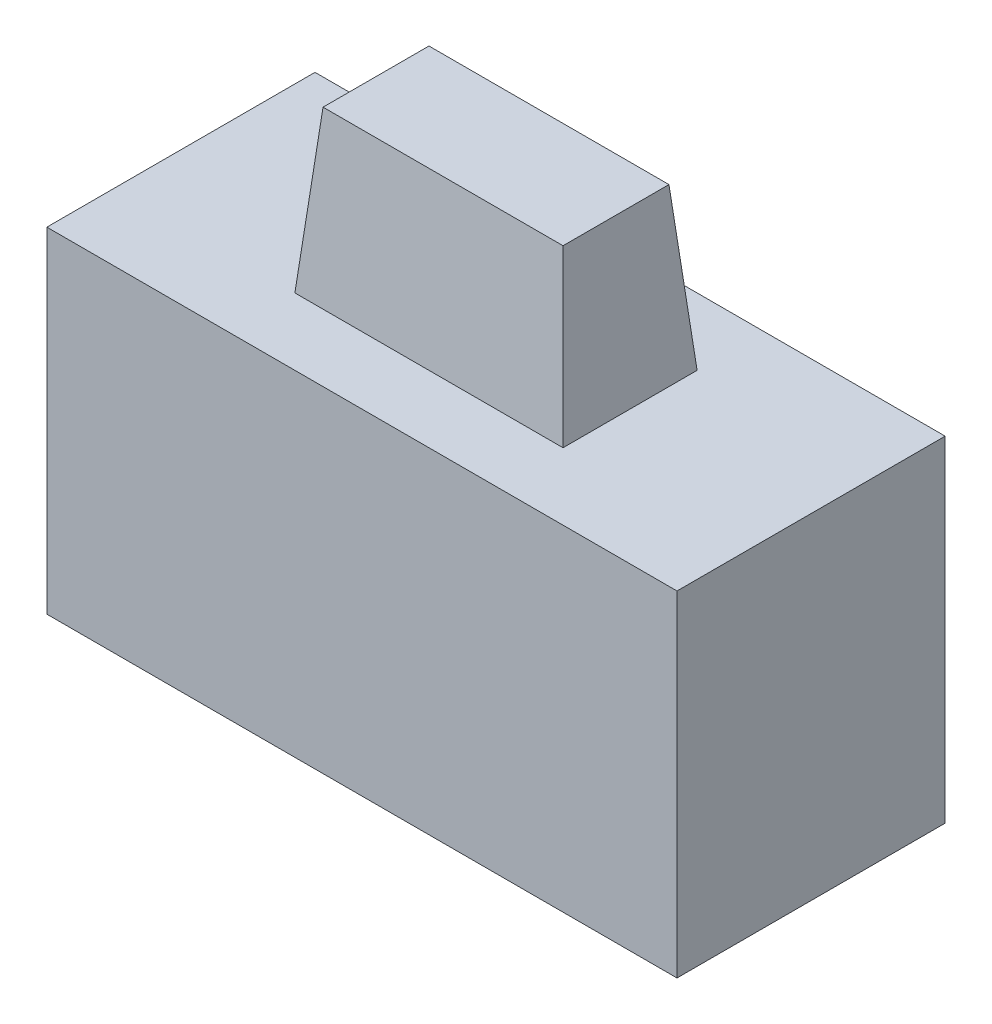
SolidWorks part; units mm, degrees
ref_plane "Front Plane" through (0, 0, 0) normal (0, 0, 1) x (1, 0, 0)
ref_plane "Top Plane" through (0, 0, 0) normal (0, 1, 0) x (1, 0, 0)
ref_plane "Right Plane" through (0, 0, 0) normal (1, 0, 0) x (0, 0, -1)
sketch "Sketch1" plane through (0, 0, 0) normal (0, 0, 1) x (1, 0, 0)
  line L1 (-2.35, 0) -> (2.35, 0)
  line L2 (-2.35, 0) -> (-2.35, -2.5)
  line L3 (-2.35, -2.5) -> (2.35, -2.5)
  line L4 (2.35, 0) -> (2.35, -2.5)
  dimension "D1" = 4.7
  dimension "D2" = 2.5
extrude "Boss-Extrude1" add sketch "Sketch1" along normal blind 2
sketch "Sketch2" plane through (0, 0, 0) normal (0, 1, 0) x (1, 0, 0)
  line L0 (0, 0) -> (0, -1) construction
  line L1 (-1, -0.5) -> (1, -0.5)
  line L2 (-1, -0.5) -> (-1, -1.5)
  line L3 (-1, -1.5) -> (1, -1.5)
  line L4 (1, -0.5) -> (1, -1.5)
  line L5 (-1, -0.5) -> (1, -1.5) construction
  line L6 (-1, -1.5) -> (1, -0.5) construction
  line L7 (0, -1) -> (0, -2) construction
  line L8 (2.35, -2) -> (-2.35, -2) construction
  point P0 (0, -1)
  dimension "D1" = 2
  dimension "D2" = 1
extrude "Boss-Extrude2" add sketch "Sketch2" along normal blind 1.2 draft 5
